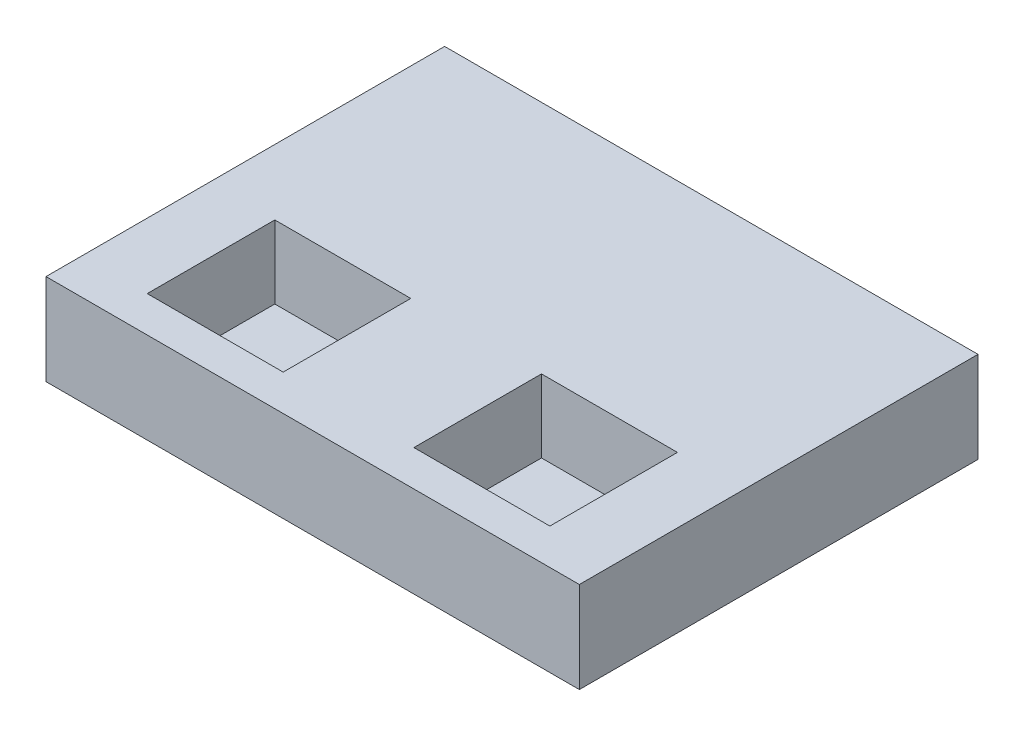
SolidWorks part; units mm, degrees
ref_plane "Płaszczyzna przednia" through (0, 0, 0) normal (0, 0, 1) x (1, 0, 0)
ref_plane "Płaszczyzna górna" through (0, 0, 0) normal (0, 1, 0) x (1, 0, 0)
ref_plane "Płaszczyzna prawa" through (0, 0, 0) normal (1, 0, 0) x (0, 0, -1)
sketch "Szkic1" plane through (0, 0, 0) normal (0, 1, 0) x (1, 0, 0)
  line L1 (-146.5, -109.5) -> (146.5, -109.5)
  line L2 (-146.5, -109.5) -> (-146.5, 109.5)
  line L3 (-146.5, 109.5) -> (146.5, 109.5)
  line L4 (146.5, -109.5) -> (146.5, 109.5)
  line L5 (-146.5, -109.5) -> (146.5, 109.5) construction
  line L6 (-146.5, 109.5) -> (146.5, -109.5) construction
  point P0 (0, 0)
  dimension "D1" = 293
  dimension "D2" = 219
extrude "Dodanie-wyciągnięcie1" add sketch "Szkic1" along normal blind 50
sketch "Szkic2" plane through (0, 50, 0) normal (0, 1, 0) x (1, 0, 0)
  line L0 (-146.5, 0) -> (146.5, 0) construction
  line L1 (-146.5, 109.5) -> (-146.5, -109.5) construction
  line L2 (146.5, -109.5) -> (146.5, 109.5) construction
  line L3 (0, 109.5) -> (0, -109.5) construction
  line L4 (146.5, 109.5) -> (-146.5, 109.5) construction
  line L5 (-146.5, -109.5) -> (146.5, -109.5) construction
  line L6 (0, 0) -> (146.5, -109.5) construction
  line L7 (-146.5, -109.5) -> (0, 0) construction
  line L8 (110.5956, -89.7967) -> (35.9044, -89.7967)
  line L9 (-110.5956, -19.7033) -> (-35.9044, -19.7033)
  line L10 (-110.5956, -19.7033) -> (-110.5956, -89.7967)
  line L11 (-110.5956, -89.7967) -> (-35.9044, -89.7967)
  line L12 (-35.9044, -19.7033) -> (-35.9044, -89.7967)
  line L13 (-110.5956, -19.7033) -> (-35.9044, -89.7967) construction
  line L14 (-110.5956, -89.7967) -> (-35.9044, -19.7033) construction
  line L15 (35.9044, -19.7033) -> (35.9044, -89.7967)
  line L16 (110.5956, -19.7033) -> (35.9044, -19.7033)
  line L17 (110.5956, -19.7033) -> (110.5956, -89.7967)
  point P16 (-73.25, -54.75)
extrude "Wytnij-wyciągnięcie1" cut sketch "Szkic2" against normal blind 40
